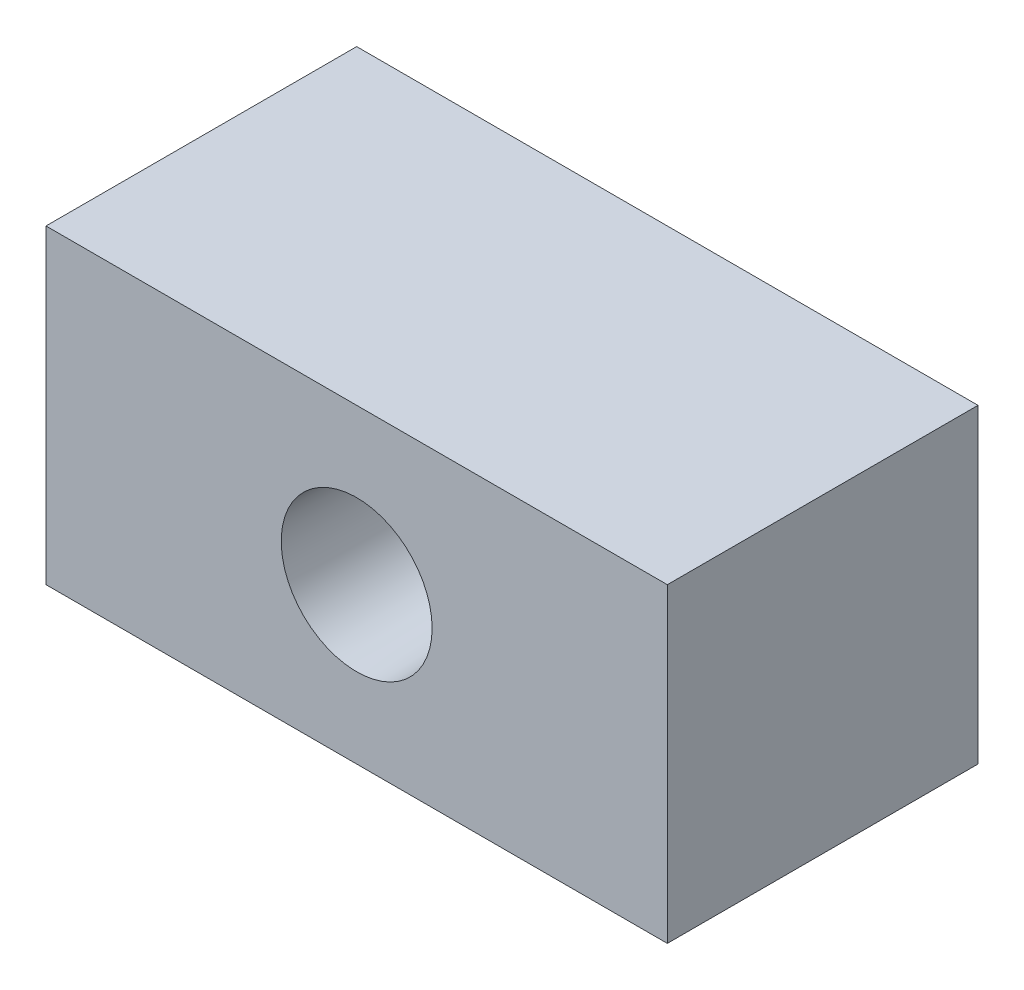
SolidWorks part; units mm, degrees
material "Сосна"
ref_plane "Front" through (0, 0, 0) normal (0, 0, 1) x (1, 0, 0)
ref_plane "Top" through (0, 0, 0) normal (0, 1, 0) x (1, 0, 0)
ref_plane "Right" through (0, 0, 0) normal (1, 0, 0) x (0, 0, -1)
sketch "Эскиз1" plane through (0, 66.7543, 0) normal (0, 0, 1) x (-1, 0, 0)
  line L7 (-7, 70.2543) -> (7, 70.2543)
  line L8 (-7, 70.2543) -> (-7, 63.2543)
  line L23 (-7, 63.2543) -> (7, 63.2543)
  line L35 (7, 70.2543) -> (7, 63.2543)
  line L36 (-7, 70.2543) -> (7, 63.2543) construction
  line L37 (-7, 63.2543) -> (7, 70.2543) construction
  point P0 (0, 66.7543)
  dimension "D1" = 7
  dimension "D2" = 14
extrude "Бобышка-Вытянуть1" add sketch "Эскиз1" along normal blind 7
sketch "Эскиз2" plane through (0, 0, 7) normal (0, 0, 1) x (1, 0, 0)
  circle A0 centre (0, 0) radius 1.7
  dimension "D1" = 3.4
extrude "Вырез-Вытянуть1" cut sketch "Эскиз2" against normal blind 6 draft 2
